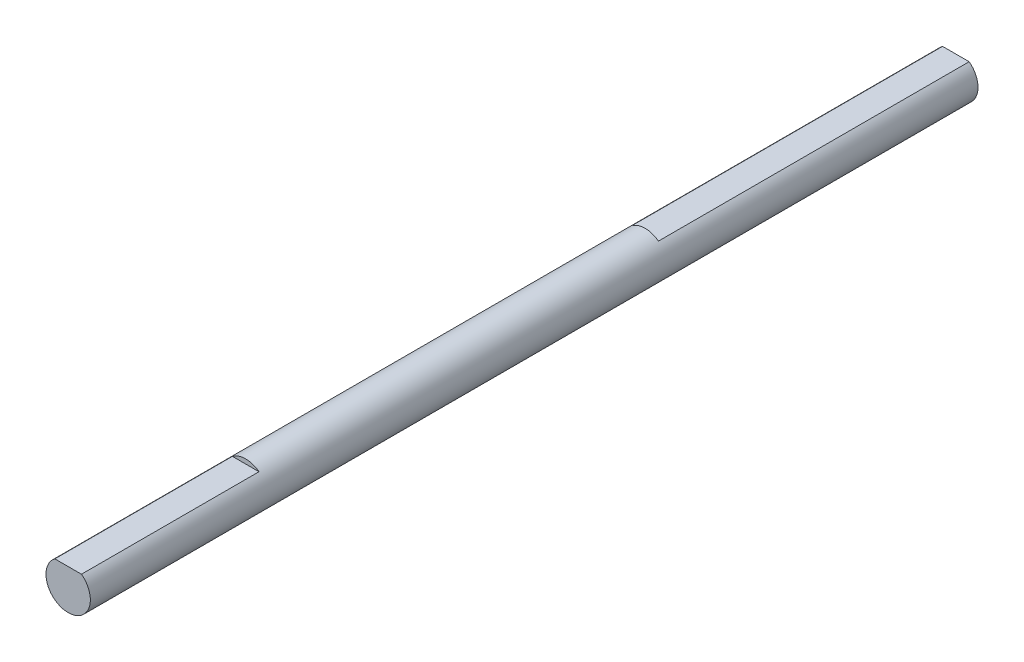
SolidWorks part; units mm, degrees
ref_plane "Front Plane" through (0, 0, 0) normal (0, 0, 1) x (1, 0, 0)
ref_plane "Top Plane" through (0, 0, 0) normal (0, 1, 0) x (1, 0, 0)
ref_plane "Right Plane" through (0, 0, 0) normal (1, 0, 0) x (0, 0, -1)
sketch "Sketch1" plane through (0, 0, 0) normal (0, 0, 1) x (1, 0, 0)
  circle A0 centre (0, 0) radius 5
  circle A1 centre (0, 0) radius 2.5
  dimension "D1" = 5
  dimension "D2" = 10
extrude "Boss-Extrude1" add sketch "Sketch1" against normal blind 200 contours A1 | A0 A1
ref_plane "Plane1" through (0, 0, -30) normal (0, 0, 1) x (1, 0, 0)
sketch "Sketch2" plane through (0, 0, 0) normal (0, 0, 1) x (1, 0, 0)
  line L0 (0, 0) -> (0, 14.4383) construction
  line L2 (-10, 6) -> (10, 6)
  line L3 (-10, 6) -> (-10, 4)
  line L4 (-10, 4) -> (10, 4)
  line L5 (10, 6) -> (10, 4)
  line L6 (-10, 6) -> (10, 4) construction
  line L7 (-10, 4) -> (10, 6) construction
  circle A0 centre (0, 0) radius 5 construction
  point P3 (0, 5)
  dimension "D1" = 20
  dimension "D2" = 2
extrude "Cut-Extrude1" cut sketch "Sketch2" against normal blind 40
ref_plane "Plane2" through (0, 0, -200) normal (0, 0, -1) x (-1, 0, 0)
sketch "Sketch4" plane through (0, 0, -200) normal (0, 0, -1) x (-1, 0, 0)
  line L1 (-10, 4) -> (10, 4)
  line L2 (-10, 4) -> (-10, 6)
  line L3 (-10, 6) -> (10, 6)
  line L4 (10, 4) -> (10, 6)
  line L5 (-10, 4) -> (10, 6) construction
  line L6 (-10, 6) -> (10, 4) construction
  point P0 (0, 5)
extrude "Cut-Extrude2" cut sketch "Sketch4" along normal through all from offset 70
